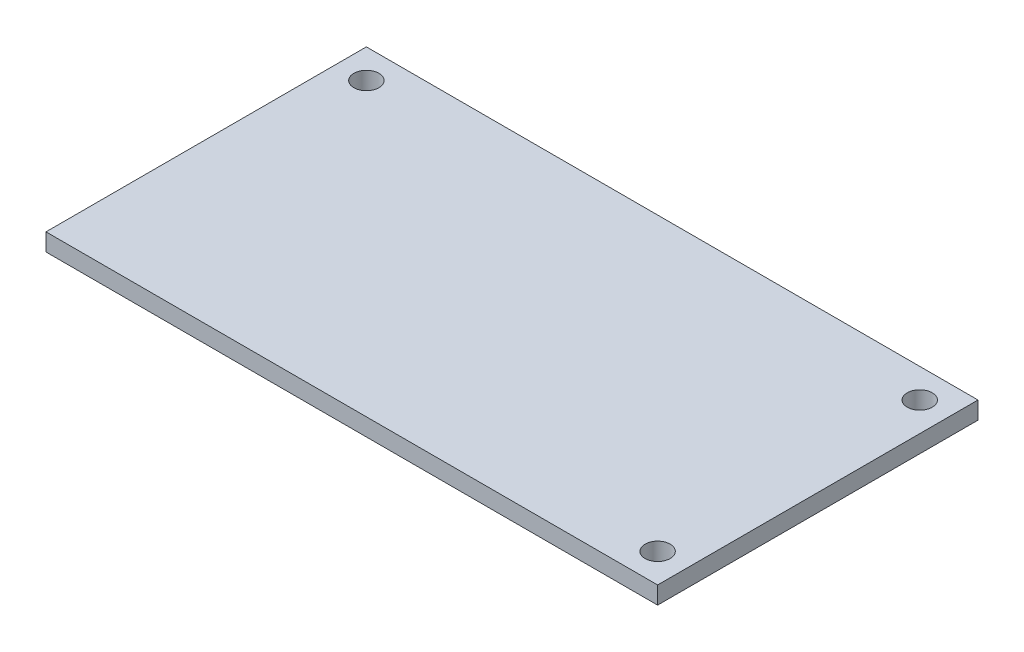
SolidWorks part; units mm, degrees
ref_plane "Front Plane" through (0, 0, 0) normal (0, 0, 1) x (1, 0, 0)
ref_plane "Top Plane" through (0, 0, 0) normal (0, 1, 0) x (1, 0, 0)
ref_plane "Right Plane" through (0, 0, 0) normal (1, 0, 0) x (0, 0, -1)
sketch "Sketch1" plane through (0, 0, 0) normal (0, 1, 0) x (1, 0, 0)
  line L1 (0, 0) -> (53.34, 0)
  line L2 (0, 0) -> (0, 27.94)
  line L3 (0, 27.94) -> (53.34, 27.94)
  line L4 (53.34, 0) -> (53.34, 27.94)
extrude "Boss-Extrude1" add sketch "Sketch1" along normal blind 1.524
sketch "Sketch2" plane through (0, 1.524, 0) normal (0, 1, 0) x (1, 0, 0)
  line L0 (53.34, 27.94) -> (0, 27.94) construction
  line L1 (0, 27.94) -> (0, 0) construction
  circle A0 centre (2.54, 25.4) radius 1.0922
  circle A1 centre (50.8, 25.4) radius 1.0922
  circle A2 centre (50.8, 2.54) radius 1.0922
  dimension "D1" = 2.1844
  dimension "D4" = 48.26
  dimension "D5" = 2.1844
  dimension "D7" = 2.1844
  dimension "D2" = 2.54
  dimension "D3" = 2.54
  dimension "D6" = 22.86
extrude "Cut-Extrude1" cut sketch "Sketch2" against normal blind 1.524
